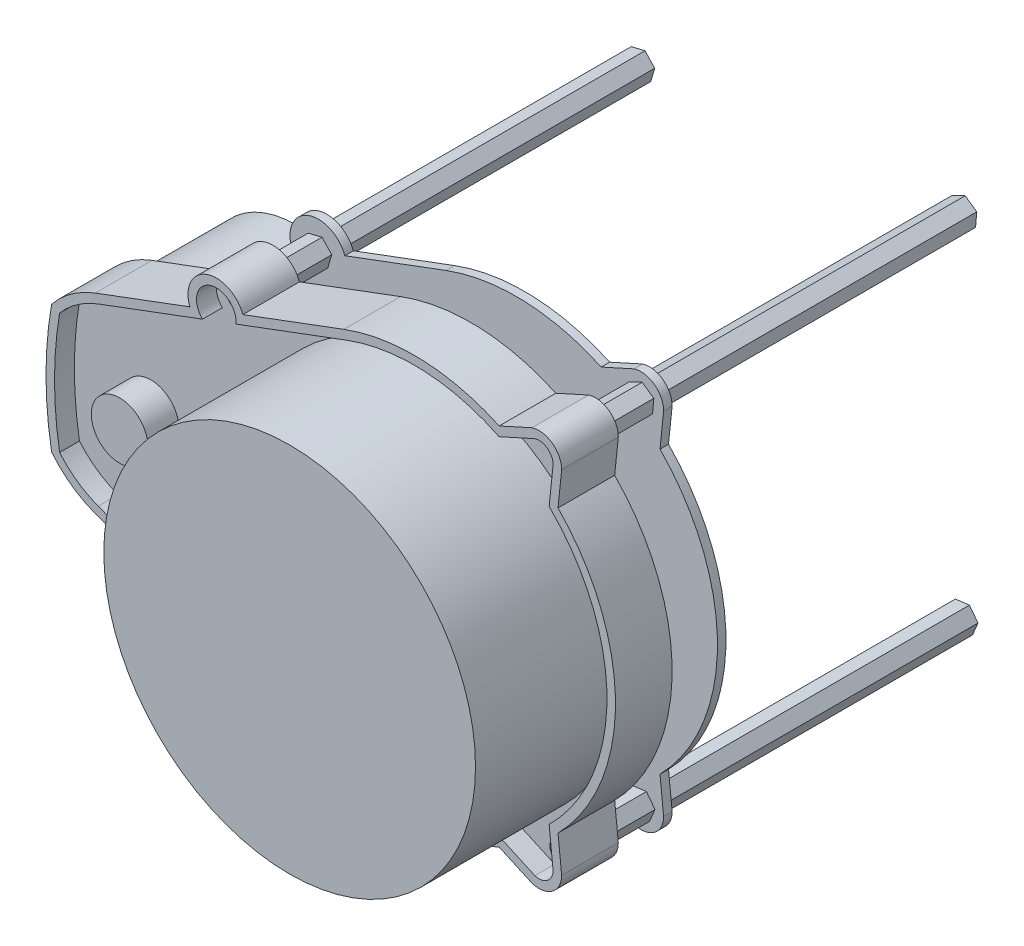
SolidWorks part; units mm, degrees
ref_plane "Plan de face" through (0, 0, 0) normal (0, 0, 1) x (1, 0, 0)
ref_plane "Plan de dessus" through (0, 0, 0) normal (0, 1, 0) x (1, 0, 0)
ref_plane "Plan de droite" through (0, 0, 0) normal (1, 0, 0) x (0, 0, -1)
sketch "Esquisse1" plane through (0, 0, 0) normal (0, 0, 1) x (1, 0, 0)
  line L0 (-12.425, 33.2546) -> (-30.2572, 26.5919)
  line L1 (-56.3, 16.8615) -> (-56.3, -16.8615) construction
  line L2 (-50, 0) -> (0, 0) construction
  line L3 (-12.425, 33.2546) -> (-12.425, -33.2546) construction
  line L5 (-35, 25) -> (-34.9409, 24.8419) construction
  line L6 (-39.6247, 23.0919) -> (-56.3, 16.8615)
  line L7 (-33.4505, 25.3988) -> (-36.4314, 24.2851)
  line L8 (20.756, 34.8016) -> (14.974, 32.1874)
  line L9 (26, 31) -> (25.36, 24.8419)
  line L10 (-65, 0) -> (35.5, 0) construction
  line L11 (55, 0) -> (-55, 0) construction
  line L12 (-35, -25) -> (-34.9409, -24.8419) construction
  line L13 (26, -31) -> (25.36, -24.8419)
  line L14 (20.756, -34.8016) -> (14.974, -32.1874)
  line L15 (-33.4505, -25.3988) -> (-36.4314, -24.2851)
  line L16 (-39.6247, -23.0919) -> (-56.3, -16.8615)
  line L17 (-12.425, -33.2546) -> (-30.2572, -26.5919)
  arc A1 (25.36, -24.8419) -> (25.36, 24.8419) centre (0, 0) ccw
  arc A3 (-64.01, 11.3013) -> (-64.01, -11.3013) centre (0, 0) ccw
  arc A4 (-56.3, 16.8615) -> (-64.01, 11.3013) centre (-50, 0) ccw
  circle A5 centre (22, 31) radius 1.6
  circle A6 centre (-35, 25) radius 1.6
  arc A7 (-30.2572, 26.5919) -> (-39.6247, 23.0919) centre (-34.9409, 24.8419) ccw
  arc A8 (26, 31) -> (20.756, 34.8016) centre (22, 31) ccw
  arc A9 (14.974, 32.1874) -> (-12.425, 33.2546) centre (0, 0) ccw
  arc A10 (14.974, -32.1874) -> (-12.425, -33.2546) centre (0, 0) cw
  arc A11 (26, -31) -> (20.756, -34.8016) centre (22, -31) cw
  arc A12 (-30.2572, -26.5919) -> (-39.6247, -23.0919) centre (-34.9409, -24.8419) cw
  circle A13 centre (-35, -25) radius 1.6
  circle A14 centre (22, -31) radius 1.6
  arc A15 (-56.3, -16.8615) -> (-64.01, -11.3013) centre (-50, 0) cw
  point P28 (-12.425, 0)
  point P29 (-56.3, 0)
  dimension "D1" = 71
  dimension "D4" = 130
  dimension "D6" = 3.2
  dimension "D10" = 10
  dimension "D11" = 8
  dimension "D3" = 50
  dimension "D5" = 31
  dimension "D7" = 22
  dimension "D8" = 35
  dimension "D9" = 25
extrude "Boss.-Extru.1" add sketch "Esquisse1" along normal blind 10 contours A15 L16 A12 L17 A10 L14 A11 L13 A1 L9 A8 L8 A9 L0 A7 L6 A4 A3 A13 A5 A6 A14
sketch "Esquisse2" plane through (0, 0, 10) normal (0, 0, 1) x (1, 0, 0)
  circle A0 centre (0, 0) radius 32.8
  dimension "D1" = 65.6
extrude "Boss.-Extru.2" add sketch "Esquisse2" along normal blind 22
sketch "Esquisse3" plane through (0, 0, 10) normal (0, 0, 1) x (1, 0, 0)
  line L16 (-55.775, -15.4564) -> (-37.3782, -22.33)
  line L17 (14.9568, -30.5335) -> (21.2911, -33.3974)
  line L18 (24.4991, -31.0687) -> (23.7942, -24.2866)
  line L19 (23.7942, 24.2866) -> (24.4991, 31.0687)
  line L20 (21.2911, 33.3974) -> (14.9568, 30.5335)
  line L21 (-11.9, 31.8495) -> (-31.4537, 24.5436)
  line L22 (-55.775, -15.4564) -> (-37.3782, -22.33)
  line L23 (14.9568, -30.5335) -> (21.2911, -33.3974)
  line L24 (24.4991, -31.0687) -> (23.7942, -24.2866)
  line L25 (23.7942, 24.2866) -> (24.4991, 31.0687)
  line L26 (21.2911, 33.3974) -> (14.9568, 30.5335)
  line L27 (-11.9, 31.8495) -> (-31.4537, 24.5436)
  line L28 (-31.4537, -24.5436) -> (-11.9, -31.8495)
  line L29 (-31.4537, -24.5436) -> (-11.9, -31.8495)
  line L30 (-37.3782, 22.33) -> (-55.775, 15.4564)
  line L31 (-37.3782, 22.33) -> (-55.775, 15.4564)
  arc A20 (-62.6, -10.6532) -> (-55.775, -15.4564) centre (-50, 0) ccw
  arc A21 (-11.9, -31.8495) -> (14.9568, -30.5335) centre (0, 0) ccw
  arc A22 (23.7942, -24.2866) -> (23.7942, 24.2866) centre (0, 0) ccw
  arc A23 (14.9568, 30.5335) -> (-11.9, 31.8495) centre (0, 0) ccw
  arc A24 (-55.775, 15.4564) -> (-62.6, 10.6532) centre (-50, 0) ccw
  arc A25 (-62.6, 10.6532) -> (-62.6, -10.6532) centre (0, 0) ccw
  arc A26 (-62.6, -10.6532) -> (-55.775, -15.4564) centre (-50, 0) ccw
  arc A27 (-11.9, -31.8495) -> (14.9568, -30.5335) centre (0, 0) ccw
  arc A28 (23.7942, -24.2866) -> (23.7942, 24.2866) centre (0, 0) ccw
  arc A29 (14.9568, 30.5335) -> (-11.9, 31.8495) centre (0, 0) ccw
  arc A30 (-55.775, 15.4564) -> (-62.6, 10.6532) centre (-50, 0) ccw
  arc A31 (-62.6, 10.6532) -> (-62.6, -10.6532) centre (0, 0) ccw
  arc A32 (-37.3782, -22.33) -> (-31.4537, -24.5436) centre (-34.9409, -24.8419) ccw
  arc A33 (-37.3782, -22.33) -> (-31.4537, -24.5436) centre (-34.9409, -24.8419) ccw
  arc A34 (21.2911, -33.3974) -> (24.4991, -31.0687) centre (22, -31) ccw
  arc A35 (21.2911, -33.3974) -> (24.4991, -31.0687) centre (22, -31) ccw
  arc A36 (24.4991, 31.0687) -> (21.2911, 33.3974) centre (22, 31) ccw
  arc A37 (24.4991, 31.0687) -> (21.2911, 33.3974) centre (22, 31) ccw
  arc A38 (-31.4537, 24.5436) -> (-37.3782, 22.33) centre (-34.9409, 24.8419) ccw
  arc A39 (-31.4537, 24.5436) -> (-37.3782, 22.33) centre (-34.9409, 24.8419) ccw
  dimension "D1" = 1.5
extrude "Enlèv. mat.-Extru.1" cut sketch "Esquisse3" against normal blind 3.5
sketch "Esquisse4" plane through (0, 0, 10) normal (0, 0, -1) x (-1, 0, 0)
  circle A1 centre (0, 0) radius 32.8
  circle A2 centre (0, 0) radius 32.8
  dimension "D1" = 0
extrude "Boss.-Extru.3" add sketch "Esquisse4" along normal up to next
sketch "Esquisse5" plane through (0, 0, 0) normal (0, 0, -1) x (-1, 0, 0)
  circle A0 centre (50, 0) radius 16
  dimension "D2" = 32
  dimension "D1" = 50
extrude "Boss.-Extru.4" add sketch "Esquisse5" along normal blind 19
sketch "Esquisse6" plane through (0, 0, 0) normal (0, 0, -1) x (-1, 0, 0)
  line L1 (-20.4892, -29.0081) -> (-22.9696, -28.6957)
  line L2 (-22.9696, -28.6957) -> (-24.4804, -30.6876)
  line L3 (-24.4804, -30.6876) -> (-23.5108, -32.9919)
  line L4 (-23.5108, -32.9919) -> (-21.0304, -33.3043)
  line L5 (-21.0304, -33.3043) -> (-19.5196, -31.3124)
  line L6 (-19.5196, -31.3124) -> (-20.4892, -29.0081)
  line L7 (36.0868, -22.7486) -> (33.5937, -22.9331)
  line L8 (33.5937, -22.9331) -> (32.5068, -25.1845)
  line L9 (32.5068, -25.1845) -> (33.9132, -27.2514)
  line L10 (33.9132, -27.2514) -> (36.4063, -27.0669)
  line L11 (36.4063, -27.0669) -> (37.4932, -24.8155)
  line L12 (37.4932, -24.8155) -> (36.0868, -22.7486)
  line L13 (36.7203, 26.814) -> (34.2892, 27.3968)
  line L14 (34.2892, 27.3968) -> (32.5689, 25.5828)
  line L15 (32.5689, 25.5828) -> (33.2797, 23.186)
  line L16 (33.2797, 23.186) -> (35.7108, 22.6032)
  line L17 (35.7108, 22.6032) -> (37.4311, 24.4172)
  line L18 (37.4311, 24.4172) -> (36.7203, 26.814)
  line L19 (-19.9522, 32.434) -> (-22.218, 33.4905)
  line L20 (-22.218, 33.4905) -> (-24.2658, 32.0565)
  line L21 (-24.2658, 32.0565) -> (-24.0478, 29.566)
  line L22 (-24.0478, 29.566) -> (-21.782, 28.5095)
  line L23 (-21.782, 28.5095) -> (-19.7342, 29.9435)
  line L24 (-19.7342, 29.9435) -> (-19.9522, 32.434)
  circle A0 centre (-22, -31) radius 2.1651 construction
  circle A1 centre (35, -25) radius 2.1651 construction
  circle A2 centre (35, 25) radius 2.1651 construction
  circle A3 centre (-22, 31) radius 2.1651 construction
  circle A4 centre (35, -25) radius 1
  circle A5 centre (35, 25) radius 1
  circle A6 centre (-22, 31) radius 1
  circle A7 centre (-22, -31) radius 1
  dimension "D2" = 2
  dimension "D1" = 5
extrude "Boss.-Extru.5" add sketch "Esquisse6" along normal blind 65
ref_plane "Plan1" through (0, 0, -8) normal (0, 0, -1) x (-1, 0, 0)
sketch "Esquisse7" plane through (0, 0, -8) normal (0, 0, -1) x (-1, 0, 0)
  line L0 (50, 0) -> (80, 0) construction
  line L8 (56.3, 16.8615) -> (39.6247, 23.0919)
  line L9 (30.2572, 26.5919) -> (12.425, 33.2546)
  line L10 (-14.974, 32.1874) -> (-20.756, 34.8016)
  line L11 (-26, 31) -> (-25.36, 24.8419)
  line L12 (-25.36, -24.8419) -> (-26, -31)
  line L13 (-20.756, -34.8016) -> (-14.974, -32.1874)
  line L14 (12.425, -33.2546) -> (30.2572, -26.5919)
  line L15 (39.6247, -23.0919) -> (56.3, -16.8615)
  line L17 (30.2572, 26.5919) -> (12.425, 33.2546)
  line L18 (-14.974, 32.1874) -> (-20.756, 34.8016)
  line L19 (-26, 31) -> (-25.36, 24.8419)
  line L20 (-25.36, -24.8419) -> (-26, -31)
  line L21 (-20.756, -34.8016) -> (-14.974, -32.1874)
  line L22 (12.425, -33.2546) -> (30.2572, -26.5919)
  arc A0 (39.6247, 23.0919) -> (39.6247, -23.0919) centre (80, 0) ccw
  arc A12 (64.69, 6.3407) -> (64.69, -6.3407) centre (50, 0) ccw
  arc A13 (64.69, 6.3407) -> (64.01, 11.3013) centre (0, 0) ccw
  arc A14 (64.01, 11.3013) -> (56.3, 16.8615) centre (50, 0) ccw
  arc A15 (39.6247, 23.0919) -> (30.2572, 26.5919) centre (34.9409, 24.8419) ccw
  arc A16 (12.425, 33.2546) -> (-14.974, 32.1874) centre (0, 0) ccw
  arc A17 (-20.756, 34.8016) -> (-26, 31) centre (-22, 31) ccw
  arc A18 (-25.36, 24.8419) -> (-25.36, -24.8419) centre (0, 0) ccw
  arc A19 (-26, -31) -> (-20.756, -34.8016) centre (-22, -31) ccw
  arc A20 (-14.974, -32.1874) -> (12.425, -33.2546) centre (0, 0) ccw
  arc A21 (30.2572, -26.5919) -> (39.6247, -23.0919) centre (34.9409, -24.8419) ccw
  arc A22 (56.3, -16.8615) -> (64.01, -11.3013) centre (50, 0) ccw
  arc A23 (64.01, -11.3013) -> (64.69, -6.3407) centre (0, 0) ccw
  arc A27 (39.6247, 23.0919) -> (30.2572, 26.5919) centre (34.9409, 24.8419) ccw
  arc A28 (12.425, 33.2546) -> (-14.974, 32.1874) centre (0, 0) ccw
  arc A29 (-20.756, 34.8016) -> (-26, 31) centre (-22, 31) ccw
  arc A30 (-25.36, 24.8419) -> (-25.36, -24.8419) centre (0, 0) ccw
  arc A31 (-26, -31) -> (-20.756, -34.8016) centre (-22, -31) ccw
  arc A32 (-14.974, -32.1874) -> (12.425, -33.2546) centre (0, 0) ccw
  arc A33 (30.2572, -26.5919) -> (39.6247, -23.0919) centre (34.9409, -24.8419) ccw
  dimension "D2" = 30
  dimension "D1" = 0
extrude "Boss.-Extru.6" add sketch "Esquisse7" along normal blind 1.5
sketch "Esquisse8" plane through (0, 0, 6.5) normal (0, 0, 1) x (1, 0, 0)
  circle A0 centre (-50, 0) radius 5
  dimension "D1" = 10
extrude "Boss.-Extru.7" add sketch "Esquisse8" along normal blind 5.5
